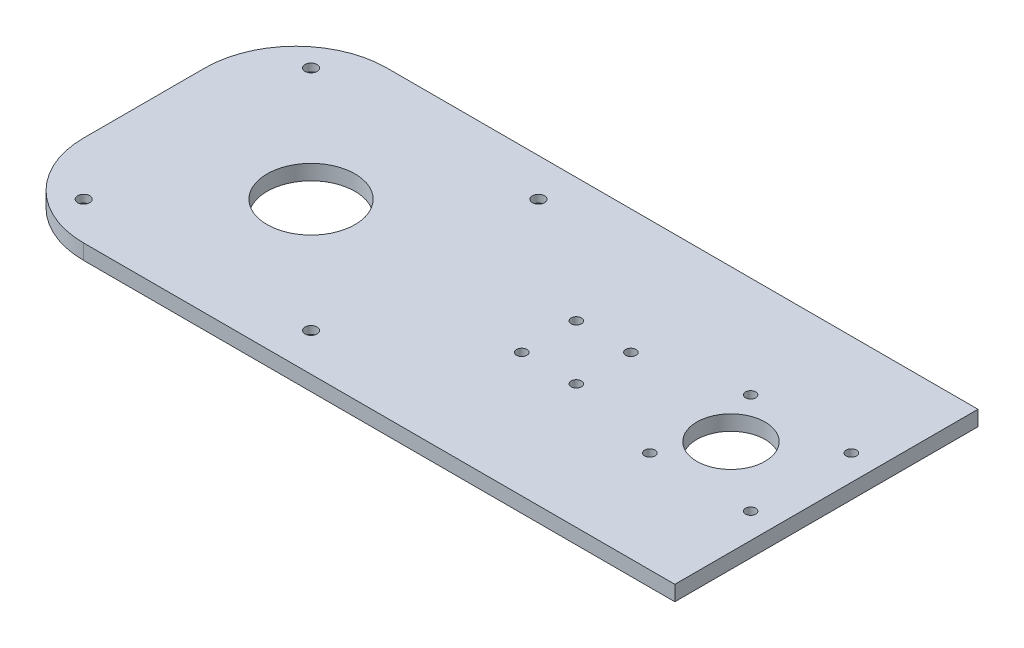
SolidWorks part; units mm, degrees
material "AISI 304"
ref_plane "前视基准面" through (0, 0, 0) normal (0, 0, 1) x (1, 0, 0)
ref_plane "上视基准面" through (0, 0, 0) normal (0, 1, 0) x (1, 0, 0)
ref_plane "右视基准面" through (0, 0, 0) normal (1, 0, 0) x (0, 0, -1)
sketch "Sketch1" plane through (0, 0, 0) normal (0, 1, 0) x (1, 0, 0)
  line L1 (225, -100) -> (-225, -100)
  line L2 (225, -100) -> (225, 100)
  line L3 (225, 100) -> (-225, 100)
  line L4 (-225, -100) -> (-225, 100)
  line L5 (225, -100) -> (-225, 100) construction
  line L6 (225, 100) -> (-225, -100) construction
  point P0 (0, 0)
  dimension "D1" = 200
  dimension "D2" = 450
extrude "Extrude1" add sketch "Sketch1" along normal blind 10
sketch "Sketch2" plane through (0, 10, 0) normal (0, 1, 0) x (1, 0, 0)
  line L0 (-115, 75) -> (-115, -75) construction
  line L1 (-40, -75) -> (-190, -75) construction
  line L2 (-40, -75) -> (-40, 75) construction
  line L3 (-40, 75) -> (-190, 75) construction
  line L4 (-190, -75) -> (-190, 75) construction
  line L5 (-40, -75) -> (-190, 75) construction
  line L6 (-40, 75) -> (-190, -75) construction
  line L7 (-40, 0) -> (-190, 0) construction
  line L8 (-225, 100) -> (-225, -100) construction
  circle A0 centre (-115, 0) radius 29
  circle A1 centre (-190, 75) radius 4
  circle A2 centre (-40, 75) radius 4
  circle A3 centre (-40, -75) radius 4
  circle A4 centre (-190, -75) radius 4
  dimension "D1" = 58
  dimension "D4" = 8
  dimension "D2" = 150
  dimension "D3" = 150
  dimension "D5" = 110
extrude "Extrude2" cut sketch "Sketch2" against normal blind 10
sketch "Sketch3" plane through (0, 10, 0) normal (0, 1, 0) x (1, 0, 0)
  line L0 (225, 0) -> (0, 0) construction
  line L1 (78, -18) -> (42, -18) construction
  line L2 (78, -18) -> (78, 18) construction
  line L3 (78, 18) -> (42, 18) construction
  line L4 (42, -18) -> (42, 18) construction
  line L5 (78, -18) -> (42, 18) construction
  line L6 (78, 18) -> (42, -18) construction
  line L7 (225, -100) -> (225, 100) construction
  line L9 (208.234, -33.234) -> (141.766, -33.234) construction
  line L10 (208.234, -33.234) -> (208.234, 33.234) construction
  line L11 (208.234, 33.234) -> (141.766, 33.234) construction
  line L12 (141.766, -33.234) -> (141.766, 33.234) construction
  line L13 (208.234, -33.234) -> (141.766, 33.234) construction
  line L14 (208.234, 33.234) -> (141.766, -33.234) construction
  circle A0 centre (175, 0) radius 47 construction
  point P0 (60, 0)
  dimension "D4" = 94
  dimension "D5" = 50
  dimension "D1" = 36
  dimension "D2" = 36
  dimension "D3" = 60
hole_wizard "M8 Tapped Hole2" positions "3DSketch2" profile "Sketch5" tap size "M8" standard "GB"
sketch3d "3DSketch2"
  point P0 (141.766, 10, -33.234)
  point P3 (208.234, 10, -33.234)
  point P6 (141.766, 10, 33.234)
  point P9 (208.234, 10, 33.234)
sketch "Sketch5" plane through (141.766, 10, -33.234) normal (1, 0, 0) x (0, 0, 1)
  line L0 (0, 0) -> (0, 21.7929)
  line L1 (0, 21.7929) -> (3.4, 19.75)
  line L2 (3.4, 19.75) -> (3.4, 0)
  line L5 (3.4, 0) -> (0, 0)
  line L10 (0, 21.7929) -> (-3.4, 19.75) construction
  line L11 (0, -6.35) -> (0, 107.95) construction
  dimension "螺纹孔钻头直径" = 6.8
  dimension "螺纹孔钻头深度" = 19.75
  dimension "导头角度" = 118
sketch "Sketch6" plane through (0, 10, 0) normal (0, 1, 0) x (1, 0, 0)
  circle A0 centre (162, 0) radius 22.5
  dimension "D1" = 45
  dimension "D2" = 13
extrude "Extrude3" cut sketch "Sketch6" against normal blind 10
sketch "Sketch7" plane through (0, 0, 0) normal (0, -1, 0) x (1, 0, 0)
  circle A5 centre (-190, 75) radius 9
  circle A6 centre (-190, 75) radius 9
  dimension "D1" = 5
extrude "Extrude4" cut sketch "Sketch7" against normal blind 5
pattern_linear "LPattern1" count 2 spacing 150 along (1, 0, 0) count 2 spacing 150 along (0, 0, -1) of "Extrude4"
hole_wizard "M8 Tapped Hole3" positions "3DSketch6" profile "Sketch11" tap size "M8" standard "GB"
sketch3d "3DSketch6"
  point P0 (42, 10, -18)
  point P3 (78, 10, -18)
  point P6 (42, 10, 18)
  point P9 (78, 10, 18)
sketch "Sketch11" plane through (42, 10, -18) normal (1, 0, 0) x (0, 0, 1)
  line L0 (0, 0) -> (0, 21.7929)
  line L1 (0, 21.7929) -> (3.4, 19.75)
  line L2 (3.4, 19.75) -> (3.4, 0)
  line L5 (3.4, 0) -> (0, 0)
  line L10 (0, 21.7929) -> (-3.4, 19.75) construction
  line L11 (0, -6.35) -> (0, 107.95) construction
  dimension "螺纹孔钻头直径" = 6.8
  dimension "螺纹孔钻头深度" = 19.75
  dimension "导头角度" = 118
fillet "Fillet1" radius 60 2 edges at (-225, 5, 100) (-225, 5, -100)
